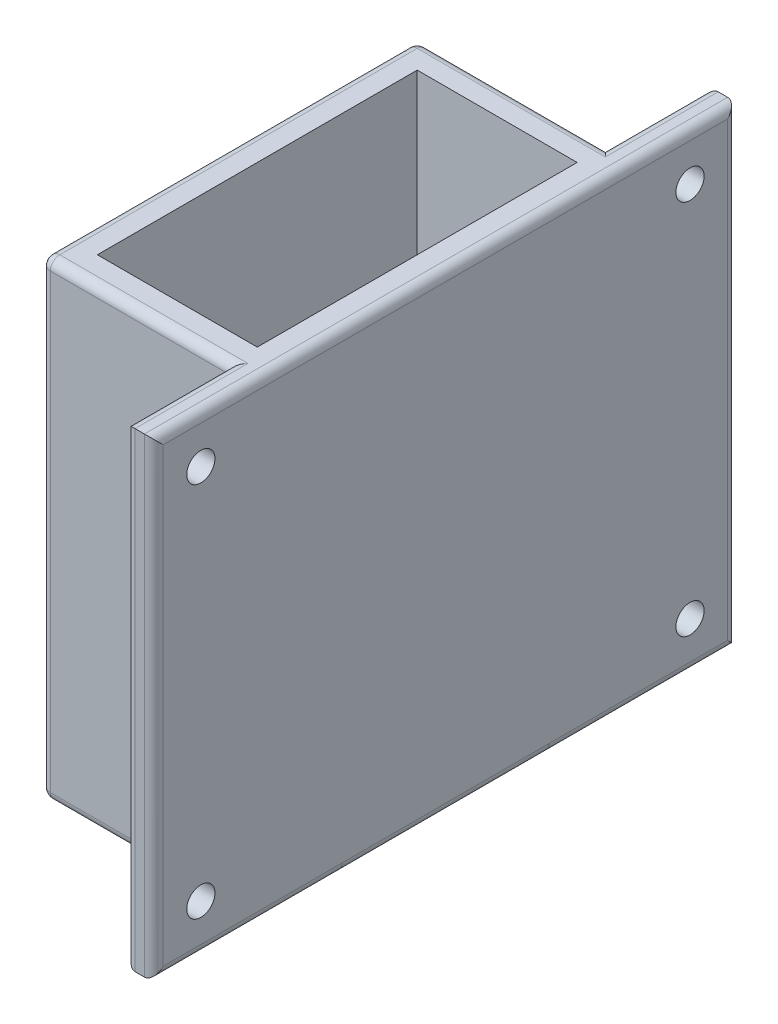
SolidWorks part; units mm, degrees
ref_plane "Alzado" through (0, 0, 0) normal (0, 0, 1) x (1, 0, 0)
ref_plane "Planta" through (0, 0, 0) normal (0, 1, 0) x (1, 0, 0)
ref_plane "Vista lateral" through (0, 0, 0) normal (1, 0, 0) x (0, 0, -1)
sketch "Croquis2" plane through (0, 0, 0) normal (0, 1, 0) x (1, 0, 0)
  line L1 (0, 0) -> (-23, 0)
  line L2 (0, 0) -> (0, 40)
  line L3 (0, 40) -> (-23, 40)
  line L4 (-23, 0) -> (-23, 40)
  dimension "D1" = 40
  dimension "D2" = 23
extrude "Saliente-Extruir1" add sketch "Croquis2" along normal blind 50
sketch "Croquis3" plane through (0, 50, 0) normal (0, 1, 0) x (1, 0, 0)
  line L0 (0, 40) -> (-23, 40) construction
  line L1 (-20, 37) -> (-3, 37)
  line L2 (-20, 37) -> (-20, 3)
  line L3 (-20, 3) -> (-3, 3)
  line L4 (-3, 37) -> (-3, 3)
  line L5 (-23, 40) -> (-23, 0) construction
  line L6 (-23, 0) -> (0, 0) construction
  line L7 (0, 0) -> (0, 40) construction
  dimension "D1" = 3
  dimension "D2" = 3
  dimension "D3" = 3
  dimension "D4" = 3
extrude "Cortar-Extruir1" cut sketch "Croquis3" against normal blind 45
fillet "Redondeo1" radius 1 8 edges at (-23, 25, -40) (0, 25, -40) (0, 25, 0) (-23, 25, 0) (-23, 0, -20) (-11.5, 0, -40) (-11.5, 0, 0) (0, 0, -20)
sketch "Croquis5" plane through (0, 0, 0) normal (1, 0, 0) x (0, 0, -1)
  line L1 (9, 50) -> (-11, 50)
  line L2 (9, 50) -> (9, 0)
  line L3 (9, 0) -> (-11, 0)
  line L4 (-11, 50) -> (-11, 0)
  line L6 (31, 50) -> (51, 50)
  line L7 (31, 50) -> (31, 0)
  line L8 (31, 0) -> (51, 0)
  line L9 (51, 50) -> (51, 0)
  line L10 (39, 1) -> (39, 50) construction
  line L12 (1, 50) -> (1, 1) construction
  line L13 (1, 50) -> (39, 50) construction
  circle A0 centre (-6, 45) radius 1.5
  circle A1 centre (-6, 5) radius 1.5
  circle A2 centre (46, 5) radius 1.5
  circle A3 centre (46, 45) radius 1.5
  dimension "D5" = 3
  dimension "D6" = 3
  dimension "D7" = 3
  dimension "D8" = 3
  dimension "D9" = 5
  dimension "D10" = 5
  dimension "D11" = 5
  dimension "D12" = 5
  dimension "D13" = 5
  dimension "D14" = 5
  dimension "D15" = 5
  dimension "D16" = 5
  dimension "D1" = 50
  dimension "D2" = 50
  dimension "D3" = 20
  dimension "D4" = 20
  dimension "D17" = 30
  dimension "D18" = 30
  dimension "D19" = 50
  dimension "D20" = 50
extrude "Saliente-Extruir3" add sketch "Croquis5" against normal blind 3
fillet "Redondeo2" radius 1 16 edges at (-12.5, 50, 0) (-22.7071, 50, -0.2929) (-23, 50, -20) (-22.7071, 50, -39.7071) (-12.5, 50, -40) (-3, 0, -45) (-3, 25, -51) (-3, 50, -45.5) (0, 25, -51) (0, 0, -41) (0, 0, 1) (0, 25, 11) (-3, 25, 11) (0, 50, -20) (-3, 50, 5.5) (-3, 0, 5)
